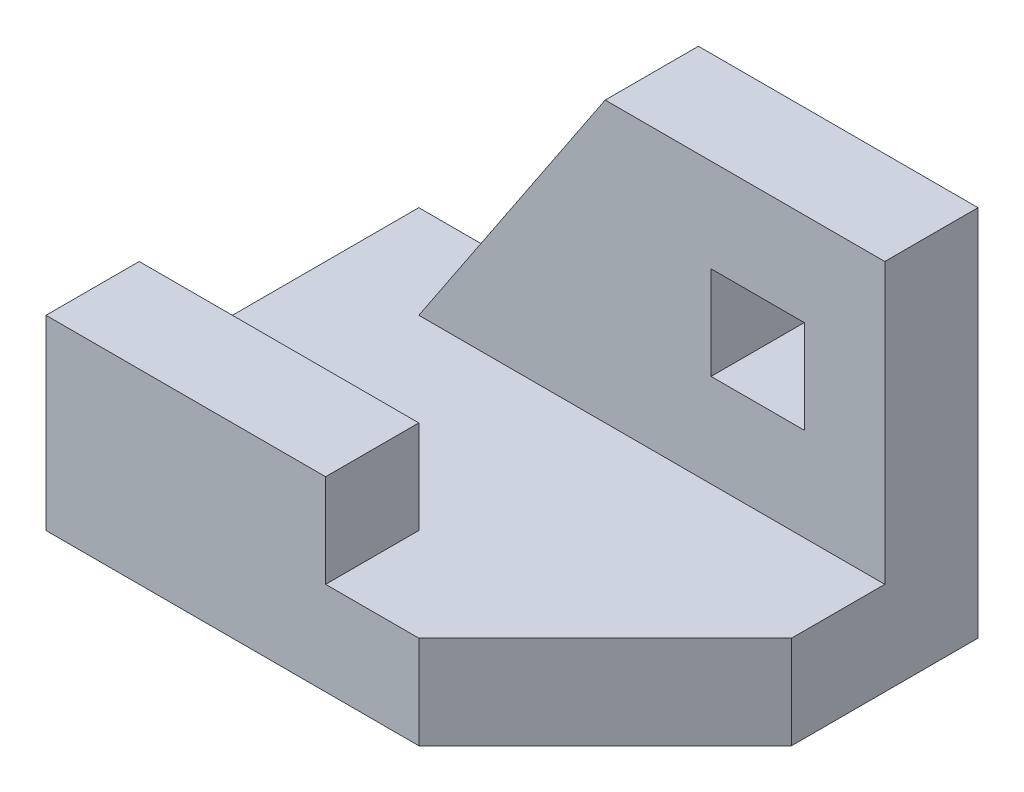
SolidWorks part; units mm, degrees
ref_plane "Front Plane" through (0, 0, 0) normal (0, 0, 1) x (1, 0, 0)
ref_plane "Top Plane" through (0, 0, 0) normal (0, 1, 0) x (1, 0, 0)
ref_plane "Right Plane" through (0, 0, 0) normal (1, 0, 0) x (0, 0, -1)
sketch "Sketch1" plane through (0, 0, 0) normal (0, 1, 0) x (1, 0, 0)
  line L0 (30, 0) -> (10, -20)
  line L1 (-30, 20) -> (30, 20)
  line L2 (-30, 20) -> (-30, -20)
  line L3 (-30, -20) -> (10, -20)
  line L4 (30, 20) -> (30, 0)
  line L5 (-30, 20) -> (18, -12) construction
  line L6 (-30, -20) -> (30, 20) construction
  point P0 (0, 0)
  dimension "D1" = 60
  dimension "D2" = 40
  dimension "D4" = 45
extrude "Boss-Extrude1" add sketch "Sketch1" along normal blind 10 contours L2 L3 L0 L4 L1
sketch "Sketch2" plane through (0, 0, 20) normal (0, 0, 1) x (1, 0, 0)
  line L1 (-30, 10) -> (0, 10)
  line L2 (-30, 10) -> (-30, 20)
  line L3 (-30, 20) -> (0, 20)
  line L4 (0, 10) -> (0, 20)
  dimension "D1" = 10
  dimension "D2" = 30
extrude "Boss-Extrude2" add sketch "Sketch2" against normal blind 10
sketch "Sketch3" plane through (0, 0, -20) normal (0, 0, -1) x (-1, 0, 0)
  line L6 (-30, 10) -> (-30, 40)
  line L11 (-30, 40) -> (0, 40)
  line L12 (-30, 10) -> (20, 10)
  line L13 (30, 10) -> (0, 10) construction
  line L14 (0, 40) -> (20, 10)
  line L15 (-21.361, 30) -> (-11.361, 30)
  line L20 (-11.361, 30) -> (-11.361, 20)
  line L21 (-11.361, 20) -> (-21.361, 20)
  line L22 (-21.361, 20) -> (-21.361, 30)
  point P9 (-16.361, 30)
  dimension "D1" = 30
  dimension "D2" = 10
  dimension "D3" = 10
  dimension "D4" = 10
extrude "Boss-Extrude3" add sketch "Sketch3" against normal blind 10
